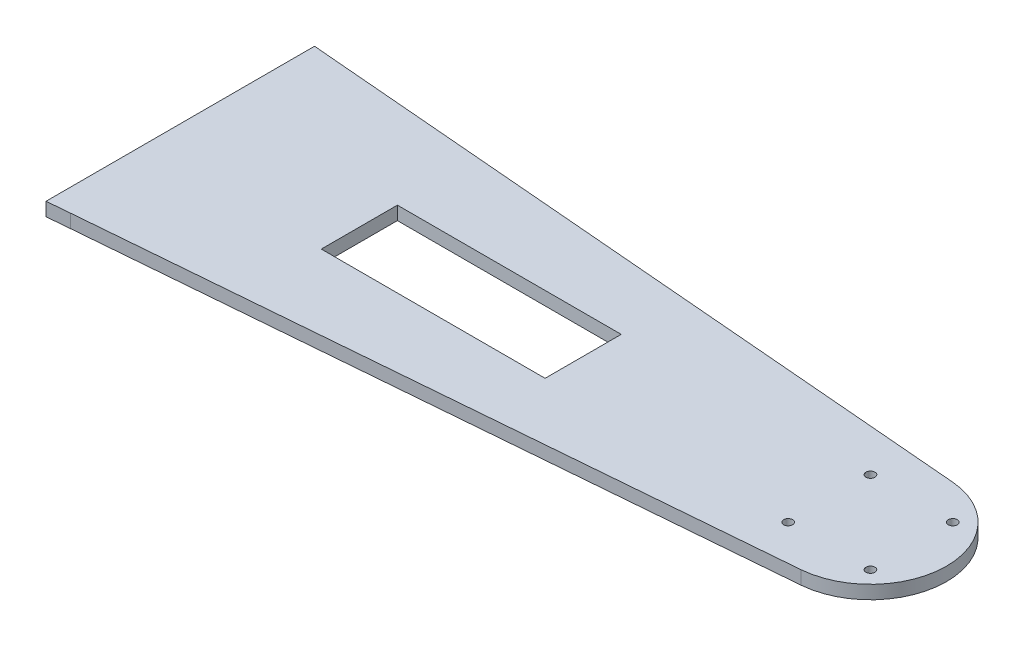
SolidWorks part; units mm, degrees
ref_plane "Front Plane" through (0, 0, 0) normal (0, 0, 1) x (1, 0, 0)
ref_plane "Top Plane" through (0, 0, 0) normal (0, 1, 0) x (1, 0, 0)
ref_plane "Right Plane" through (0, 0, 0) normal (1, 0, 0) x (0, 0, -1)
sketch "Sketch1" plane through (0, 0, 0) normal (0, 1, 0) x (1, 0, 0)
  line L0 (0, 0) -> (150.6121, 12.6219)
  line L1 (150.6121, 46.5032) -> (149.1924, 29.5626) construction
  line L2 (150.6121, 46.5032) -> (0, 59.1251)
  line L3 (0, 59.1251) -> (0, 0) construction
  line L4 (149.1924, 29.5626) -> (150.6121, 12.6219) construction
  line L5 (149.1924, 29.5626) -> (0, 29.5626) construction
  line L6 (140, 38.7549) -> (158.3848, 38.7549) construction
  line L7 (158.3848, 38.7549) -> (158.3848, 20.3702) construction
  line L8 (158.3848, 20.3702) -> (140, 20.3702) construction
  line L9 (140, 20.3702) -> (140, 38.7549) construction
  line L10 (140, 38.7549) -> (158.3848, 20.3702) construction
  line L11 (140, 20.3702) -> (158.3848, 38.7549) construction
  line L12 (0, 59.1251) -> (-5, 59.5626)
  line L13 (-5, 59.5626) -> (-5, -0.4374)
  line L14 (-5, -0.4374) -> (0, 0)
  line L15 (0, 29.5626) -> (-5, 29.5626) construction
  arc A0 (150.6121, 46.5032) -> (150.6121, 12.6219) centre (149.1924, 29.5626) cw
  circle A1 centre (140, 38.7549) radius 1
  circle A2 centre (140, 20.3702) radius 1
  circle A3 centre (158.3848, 20.3702) radius 1
  circle A4 centre (158.3848, 38.7549) radius 1
  point P13 (149.1924, 29.5626)
  dimension "D1" = 140
  dimension "D3" = 17
  dimension "D5" = 2
  dimension "D7" = 149.1924
  dimension "D2" = 60
  dimension "D4" = 26
  dimension "D6" = 45
  dimension "D8" = 5
  dimension "D9" = 5
  dimension "D10" = 154.1924
extrude "Boss-Extrude1" add sketch "Sketch1" along normal blind 3
sketch "Sketch2" plane through (0, 3, 0) normal (0, 1, 0) x (1, 0, 0)
  line L0 (35, 29.5626) -> (-5, 29.5626) construction
  line L1 (35, 38.0626) -> (85, 38.0626)
  line L2 (35, 38.0626) -> (35, 21.0626)
  line L3 (35, 21.0626) -> (85, 21.0626)
  line L4 (85, 38.0626) -> (85, 21.0626)
  line L5 (-5, 59.5626) -> (-5, -0.4374) construction
  dimension "D1" = 17
  dimension "D2" = 50
  dimension "D3" = 40
extrude "Cut-Extrude1" cut sketch "Sketch2" against normal through all
